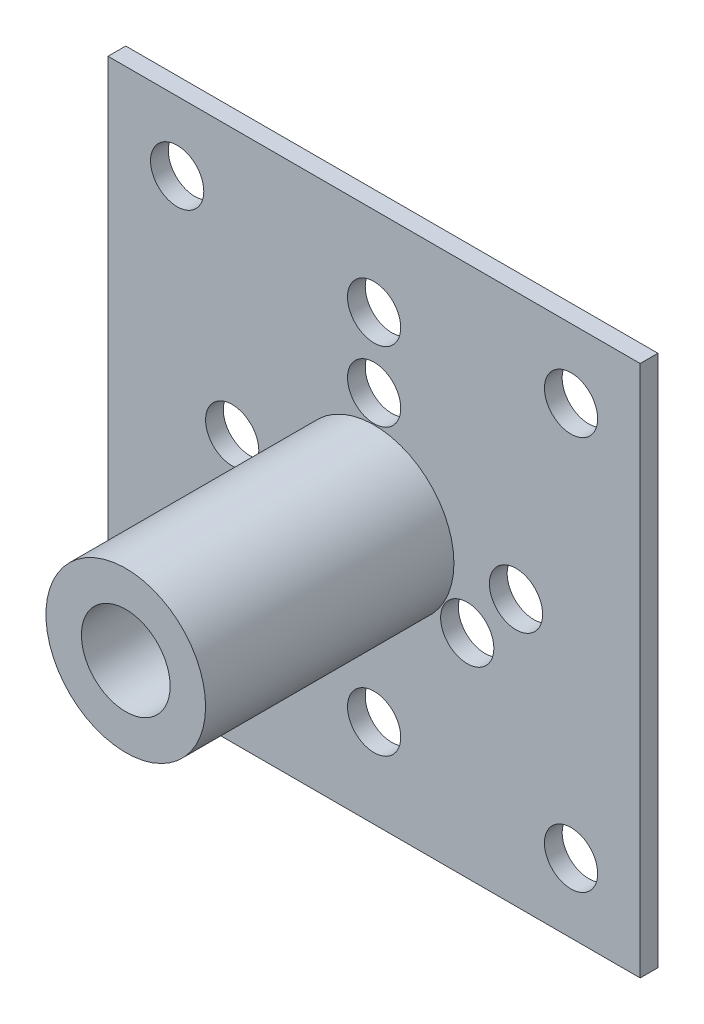
SolidWorks part; units mm, degrees
ref_plane "Front Plane" through (0, 0, 0) normal (0, 0, 1) x (1, 0, 0)
ref_plane "Top Plane" through (0, 0, 0) normal (0, 1, 0) x (1, 0, 0)
ref_plane "Right Plane" through (0, 0, 0) normal (1, 0, 0) x (0, 0, -1)
sketch "Sketch2" plane through (0, 0, 0) normal (0, 0, 1) x (1, 0, 0)
  circle A0 centre (0, 0) radius 2.5
  circle A1 centre (0, 0) radius 4.5
  dimension "D1" = 9
  dimension "D2" = 2
sketch "Sketch3" plane through (0, 0, 0) normal (0, 0, 1) x (1, 0, 0)
  line L1 (15, -15) -> (-15, -15)
  line L2 (15, -15) -> (15, 15)
  line L3 (15, 15) -> (-15, 15)
  line L4 (-15, -15) -> (-15, 15)
  line L5 (15, -15) -> (-15, 15) construction
  line L6 (15, 15) -> (-15, -15) construction
  point P0 (0, 0)
  dimension "D1" = 30
extrude "Boss-Extrude4" add sketch "Sketch2" along normal blind 15
extrude "Boss-Extrude5" add sketch "Sketch3" along normal blind 1
sketch "Sketch6" plane through (0, 0, 0) normal (0, 0, 1) x (1, 0, 0)
  line L0 (0, -15) -> (0, 15) construction
  line L1 (-15, -15) -> (15, -15) construction
  line L2 (15, 15) -> (-15, 15) construction
  line L3 (-15, 0) -> (15, 0) construction
  line L4 (-15, 15) -> (-15, -15) construction
  line L5 (15, -15) -> (15, 15) construction
  line L6 (-11.1016, -11.1016) -> (0, 0) construction
  circle A2 centre (-11.1016, -11.1016) radius 1.5
  circle A3 centre (11.1016, -11.1016) radius 1.5
  circle A4 centre (11.1016, 11.1016) radius 1.5
  circle A5 centre (-11.1016, 11.1016) radius 1.5
  circle A6 centre (0, 0) radius 15.7 construction
  circle A7 centre (0, -10) radius 1.5
  circle A8 centre (0, 10) radius 1.5
  circle A9 centre (-8, 0) radius 1.5
  circle A10 centre (8, 0) radius 1.5
  circle A14 centre (0, 6.0622) radius 1.5
  circle A17 centre (5.25, -3.0311) radius 1.5
  circle A18 centre (-5.25, -3.0311) radius 1.5
  circle A19 centre (0, 0) radius 2.5
  circle A20 centre (0, 0) radius 2.5 construction
  point P39 (0, 0)
  point P40 (0, 0)
  point P41 (0, 0)
  dimension "D1" = 31.4
  dimension "D3" = 3
  dimension "D9" = 3
  dimension "D11" = 10.5
  dimension "D2" = 45
  dimension "D5" = 20
  dimension "D7" = 16
extrude "Cut-Extrude4" cut sketch "Sketch6" along normal blind 20
